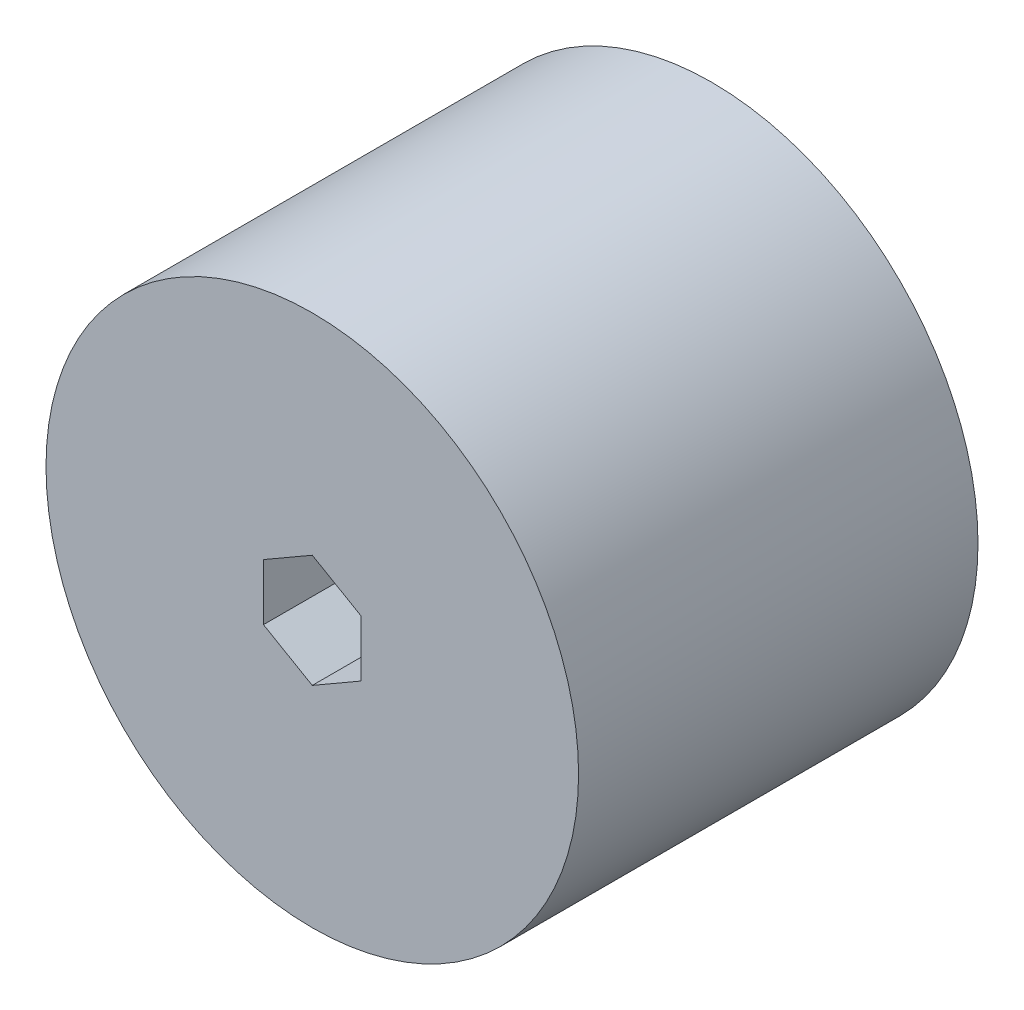
SolidWorks part; units mm, degrees
material "PET"
ref_plane "Front Plane" through (0, 0, 0) normal (0, 0, 1) x (1, 0, 0)
ref_plane "Top Plane" through (0, 0, 0) normal (0, 1, 0) x (1, 0, 0)
ref_plane "Right Plane" through (0, 0, 0) normal (1, 0, 0) x (0, 0, -1)
sketch "Sketch1" plane through (0, 0, 0) normal (0, 0, 1) x (1, 0, 0)
  line L1 (0, 8.0656) -> (-6.985, 4.0328)
  line L2 (-6.985, 4.0328) -> (-6.985, -4.0328)
  line L3 (-6.985, -4.0328) -> (0, -8.0656)
  line L4 (0, -8.0656) -> (6.985, -4.0328)
  line L5 (6.985, -4.0328) -> (6.985, 4.0328)
  line L6 (6.985, 4.0328) -> (0, 8.0656)
  circle A0 centre (0, 0) radius 38.1
  circle A1 centre (0, 0) radius 6.985 construction
  dimension "D1" = 76.2
  dimension "D2" = 13.97
extrude "Boss-Extrude1" add sketch "Sketch1" along normal blind 57.15
